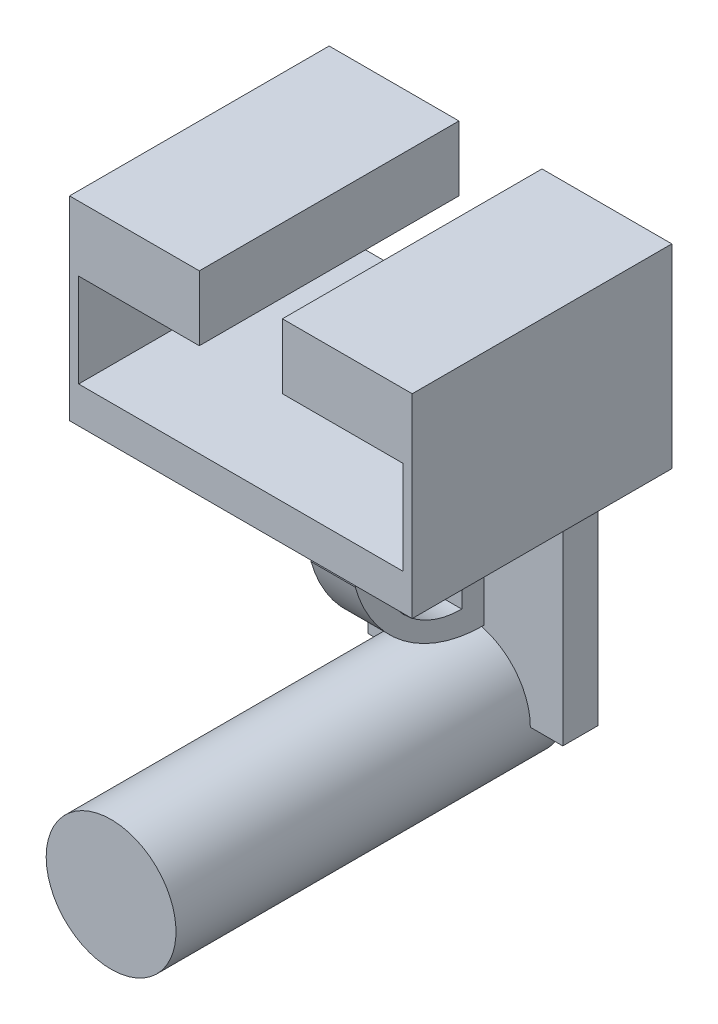
SolidWorks part; units mm, degrees
material "6061-T6 (SS)"
ref_plane "Front Plane" through (0, 0, 0) normal (0, 0, 1) x (1, 0, 0)
ref_plane "Top Plane" through (0, 0, 0) normal (0, 1, 0) x (1, 0, 0)
ref_plane "Right Plane" through (0, 0, 0) normal (1, 0, 0) x (0, 0, -1)
sketch "Sketch3" plane through (0, 0, 0) normal (0, 0, 1) x (1, 0, 0)
  line L0 (19.05, 50.8) -> (19.05, 0) construction
  line L1 (0, 0) -> (6.35, 0)
  line L2 (0, 0) -> (0, 50.8)
  line L3 (0, 50.8) -> (38.1, 50.8)
  line L4 (38.1, 0) -> (38.1, 50.8)
  line L5 (31.75, 0) -> (38.1, 0)
  arc A0 (31.75, 0) -> (6.35, 0) centre (19.05, 0) ccw
  arc A1 (6.35, 0) -> (31.75, 0) centre (19.05, 0) cw
  dimension "D1" = 50.8
  dimension "D2" = 38.1
extrude "Boss-Extrude4" add sketch "Sketch3" along normal blind 6.858 contours A1 L5 L4 L3 L2 L1
sketch "Sketch7" plane through (0, 0, 0) normal (0, 0, -1) x (-1, 0, 0)
  line L0 (-38.1, 0) -> (0, 0) construction
  line L1 (-19.05, 50.8) -> (-19.05, 0) construction
  line L2 (0, 50.8) -> (-38.1, 50.8) construction
  circle A0 centre (-19.05, 0) radius 12.7
  dimension "D1" = 25.4
extrude "Boss-Extrude5" add sketch "Sketch7" against normal blind 76.2
sketch "Sketch9" plane through (0, 50.8, 0) normal (0, 1, 0) x (1, 0, 0)
  line L0 (19.05, 0) -> (19.05, -6.858) construction
  line L1 (0, 0) -> (38.1, 0) construction
  line L2 (0, -6.858) -> (38.1, -6.858) construction
  line L3 (0, -3.429) -> (19.05, -3.429) construction
  line L4 (0, -6.858) -> (0, 0) construction
  line L5 (19.05, -50.8) -> (19.05, 0) construction
  line L6 (-12.7, 0) -> (50.8, 0)
  line L7 (-12.7, 0) -> (-12.7, -50.8)
  line L8 (-12.7, -50.8) -> (50.8, -50.8)
  line L9 (50.8, 0) -> (50.8, -50.8)
  dimension "D1" = 63.5
  dimension "D2" = 50.8
  dimension "D3" = 0
extrude "Boss-Extrude6" add sketch "Sketch9" along normal blind 7.112
sketch "Sketch11" plane through (50.8, 0, 0) normal (1, 0, 0) x (0, 0, -1)
  line L0 (-25.4, 57.912) -> (-25.4, 50.8) construction
  line L1 (-50.8, 57.912) -> (0, 57.912) construction
  line L2 (-50.8, 50.8) -> (0, 50.8) construction
  line L3 (-50.8, 54.356) -> (-25.4, 54.356) construction
  line L4 (-50.8, 57.912) -> (-50.8, 50.8) construction
  line L5 (-25.4, 50.8) -> (-25.4, 88.9) construction
  line L6 (-50.8, 88.9) -> (0, 88.9)
  line L7 (-50.8, 88.9) -> (-50.8, 50.8)
  line L8 (-50.8, 50.8) -> (0, 50.8)
  line L9 (0, 88.9) -> (0, 50.8)
  dimension "D1" = 38.1
  dimension "D2" = 50.8
extrude "Boss-Extrude7" add sketch "Sketch11" along normal blind 1.778
sketch "Sketch12" plane through (-12.7, 0, 0) normal (-1, 0, 0) x (0, 0, 1)
  line L6 (0, 88.9) -> (50.8, 88.9)
  line L7 (0, 88.9) -> (0, 50.8)
  line L8 (0, 50.8) -> (50.8, 50.8)
  line L9 (50.8, 88.9) -> (50.8, 50.8)
  dimension "D1" = 38.1
  dimension "D2" = 50.8
extrude "Boss-Extrude8" add sketch "Sketch12" along normal blind 1.778
sketch "Sketch14" plane through (0, 88.9, 0) normal (0, 1, 0) x (1, 0, 0)
  line L1 (52.578, 0) -> (27.178, 0)
  line L2 (52.578, 0) -> (52.578, -50.8)
  line L3 (52.578, -50.8) -> (27.178, -50.8)
  line L4 (27.178, 0) -> (27.178, -50.8)
  dimension "D1" = 50.8
  dimension "D2" = 25.4
extrude "Boss-Extrude9" add sketch "Sketch14" against normal blind 12.7
sketch "Sketch15" plane through (0, 88.9, 0) normal (0, 1, 0) x (1, 0, 0)
  line L1 (-14.478, 0) -> (10.922, 0)
  line L2 (-14.478, 0) -> (-14.478, -50.8)
  line L3 (-14.478, -50.8) -> (10.922, -50.8)
  line L4 (10.922, 0) -> (10.922, -50.8)
  dimension "D1" = 50.8
  dimension "D2" = 25.4
extrude "Boss-Extrude10" add sketch "Sketch15" against normal blind 12.7
sketch "Sketch19" plane through (0, 0, 0) normal (0, 0, 1) x (1, 0, 0)
  line L8 (13.9825, 12.7) -> (22.6357, 12.7)
  line L9 (22.6357, 12.7) -> (22.6357, 50.8)
  line L10 (22.6357, 50.8) -> (13.9825, 50.8)
  line L11 (13.9825, 50.8) -> (13.9825, 12.7)
  point P3 (0, 50.8)
extrude "Boss-Extrude11" add sketch "Sketch19" along normal blind 32.004 separate body
sketch "Sketch26" plane through (13.9825, 0, 0) normal (-1, 0, 0) x (0, 0, 1)
  line L7 (6.858, 0) -> (6.858, 12.7) construction
  line L9 (32.004, 50.8) -> (32.004, 12.7) construction
  line L10 (32.004, 31.75) -> (32.004, 12.7)
  line L11 (32.004, 12.7) -> (6.858, 12.7)
  arc A0 (6.858, 12.7) -> (32.004, 31.75) centre (6.858, 38.8214) ccw
extrude "Cut-Extrude4" cut sketch "Sketch26" against normal up to vertex (8.6532 mm away)
sketch "Sketch28" plane through (13.9825, 0, 0) normal (-1, 0, 0) x (0, 0, 1)
  line L0 (11.1581, 47.1851) -> (11.1581, 17.6116)
  line L1 (11.1581, 47.1851) -> (27.0726, 47.1851)
  line L2 (27.0726, 47.1851) -> (27.0726, 32.3983)
  arc A0 (11.1581, 17.6116) -> (27.0726, 32.3983) centre (11.1581, 33.5691) ccw
extrude "Cut-Extrude5" cut sketch "Sketch28" against normal up to vertex (8.6532 mm away)
equation "\"ShaftL\"= 3in"
equation "\"ShaftD\"= 1in"
equation "\"BWidth\"= 1.5in"
equation "\"BLength\"= 2in"
equation "\"BThickness\"= 0.27in"
equation "\"CLegth\"= 2.5in"
equation "\"CWidth\"= 2in"
equation "\"CHeight\"= 0.28in"
equation "\"DLength\"= 2in"
equation "\"DWidth\"= 1.498in"
equation "\"DThickness\"= 0.07in"
equation "\"ELength\"= 2in"
equation "\"EWidth\"= 0.9990"
equation "\"EHeight\"= 0.5in"
